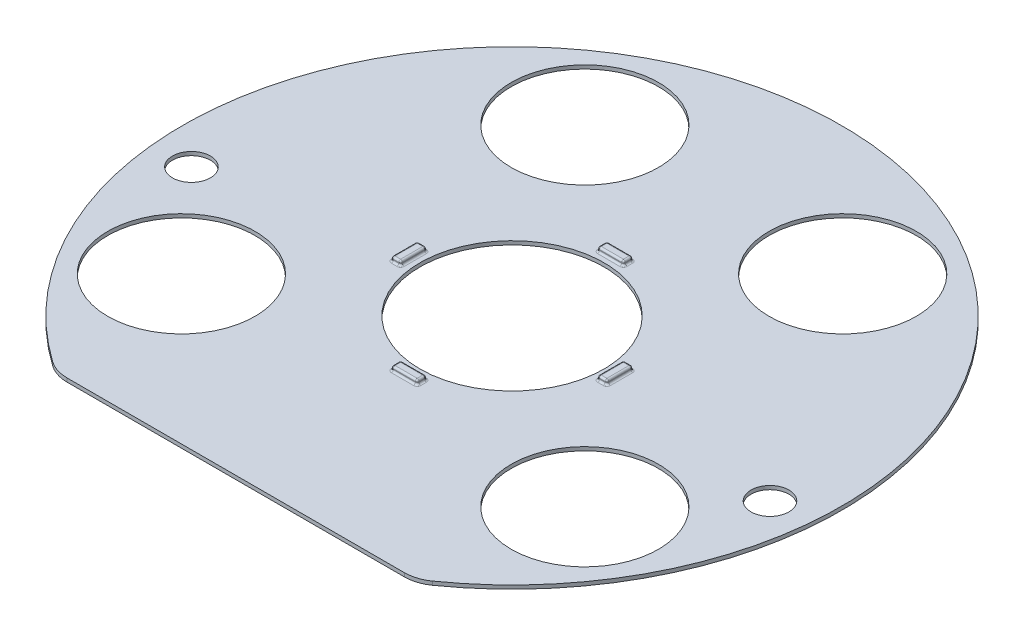
SolidWorks part; units mm, degrees
material "6063-T6"
ref_plane "Front Plane" through (0, 0, 0) normal (0, 0, 1) x (1, 0, 0)
ref_plane "Top Plane" through (0, 0, 0) normal (0, 1, 0) x (1, 0, 0)
ref_plane "Right Plane" through (0, 0, 0) normal (1, 0, 0) x (0, 0, -1)
sketch "Sketch1" plane through (0, 0, 0) normal (0, 1, 0) x (1, 0, 0)
  line L0 (0, 89.5) -> (0, -75) construction
  line L2 (-89.5, 0) -> (89.5, 0) construction
  line L3 (-48.839, -75) -> (48.839, -75)
  arc A0 (48.839, -75) -> (-48.839, -75) centre (0, 0) ccw
  dimension "D1" = 179
  dimension "D2" = 75
extrude "Boss-Extrude1" add sketch "Sketch1" against normal blind 1
sketch "Sketch9" plane through (0, 0, 0) normal (0, 1, 0) x (1, 0, 0)
  line L0 (0, 89.5) -> (0, -75) construction
  line L1 (48.839, -75) -> (-48.839, -75) construction
  line L2 (78.5412, -8.5017) -> (-78.5412, -8.5017) construction
  arc A12 (48.839, -75) -> (-48.839, -75) centre (0, 0) ccw construction
  circle A13 centre (78.5412, -8.5017) radius 5.15
  circle A15 centre (-78.5412, -8.5017) radius 5.15
  point P8 (0, -8.5017)
  dimension "D3" = 10.3
  dimension "D4" = 10.3
  dimension "D2" = 66.4983
  dimension "D1" = 157.0824
extrude "Cut-Extrude3" cut sketch "Sketch9" against normal through all
sketch "Vision Pattern" plane through (0, 0, 0) normal (0, 1, 0) x (1, 0, 0)
  line L0 (64.8074, -55) -> (-64.8074, -55) construction
  line L1 (0, 0) -> (0, -55) construction
  circle A0 centre (0, 0) radius 85 construction
  circle A1 centre (0, 0) radius 25
  circle A2 centre (54.7723, -35) radius 20
  circle A3 centre (-54.7723, -35) radius 20
  circle A4 centre (35, 54.7723) radius 20
  circle A5 centre (-35, 54.7723) radius 20
  circle A6 centre (0, 0) radius 65 construction
  dimension "D1" = 170
  dimension "D3" = 50
  dimension "D4" = 40
  dimension "D2" = 55
  dimension "D5" = 35
  dimension "D8" = 65
  dimension "D6" = 35
  dimension "D7" = 35
extrude "Cut-Extrude4" cut sketch "Vision Pattern" against normal through all
sketch "Sketch10" plane through (0, 0, 0) normal (0, 1, 0) x (1, 0, 0)
  line L0 (0, 28) -> (0, -28) construction
  line L1 (-28, 0) -> (28, 0) construction
  line L2 (3.5, 26.75) -> (-3.5, 26.75)
  line L3 (-26.75, 3.5) -> (-29.25, 3.5)
  line L4 (-26.75, 3.5) -> (-26.75, -3.5)
  line L5 (-26.75, -3.5) -> (-29.25, -3.5)
  line L6 (-29.25, 3.5) -> (-29.25, -3.5)
  line L7 (-26.75, 3.5) -> (-29.25, -3.5) construction
  line L8 (-26.75, -3.5) -> (-29.25, 3.5) construction
  line L9 (3.5, 26.75) -> (3.5, 29.25)
  line L10 (3.5, 29.25) -> (-3.5, 29.25)
  line L11 (-3.5, 26.75) -> (-3.5, 29.25)
  line L12 (26.75, -3.5) -> (26.75, 3.5)
  line L13 (26.75, -3.5) -> (29.25, -3.5)
  line L14 (29.25, -3.5) -> (29.25, 3.5)
  line L15 (26.75, 3.5) -> (29.25, 3.5)
  line L16 (-3.5, -26.75) -> (3.5, -26.75)
  line L17 (-3.5, -26.75) -> (-3.5, -29.25)
  line L18 (-3.5, -29.25) -> (3.5, -29.25)
  line L19 (3.5, -26.75) -> (3.5, -29.25)
  line L20 (-3.5, 29.25) -> (3.5, 26.75) construction
  line L21 (3.5, 29.25) -> (-3.5, 26.75) construction
  point P4 (0, 0)
  point P8 (0, 0)
  point P27 (0, 0)
  dimension "D1" = 56
  dimension "D2" = 7
  dimension "D3" = 2.5
fillet "Fillet1" radius 10 2 edges at (-48.839, -0.5, 75) (48.839, -0.5, 75)
extrude "Boss-Extrude2" add sketch "Sketch10" along normal blind 1.2
fillet "Fillet2" radius 0.5 48 edges at (-3.5, 0.6, 26.75) (3.5, 0.6, 29.25) (3.5, 0.6, 26.75) (26.75, 0.6, 3.5) (29.25, 0.6, 3.5) (29.25, 0.6, -3.5) (26.75, 0.6, -3.5) (3.5, 0.6, -26.75) (3.5, 0.6, -29.25) (-3.5, 0.6, -29.25) (-3.5, 0.6, -26.75) (-26.75, 0.6, 3.5) (-26.75, 0.6, -3.5) (-29.25, 0.6, -3.5) (-29.25, 0.6, 3.5) (-3.5, 0.6, 29.25) (0, 0, -29.25) (29.25, 0, 0) (0, 0, 26.75) (-26.75, 0, 0) (-3.5, 0, -28) (3.5, 0, -28) (28, 0, -3.5) (28, 0, 3.5) (-3.5, 0, 28) (3.5, 0, 28) (-28, 0, -3.5) (-28, 0, 3.5) (0, 1.2, -29.25) (3.5, 1.2, -28) (0, 1.2, -26.75) (-3.5, 1.2, -28) (29.25, 1.2, 0) (28, 1.2, 3.5) (26.75, 1.2, 0) (28, 1.2, -3.5) (0, 1.2, 29.25) (-3.5, 1.2, 28) (0, 1.2, 26.75) (3.5, 1.2, 28) (-28, 1.2, -3.5) (-26.75, 1.2, 0) (-28, 1.2, 3.5) (-29.25, 1.2, 0) (0, 0, -26.75) (26.75, 0, 0) (0, 0, 29.25) (-29.25, 0, 0)
equation "\"D4@Sketch9\"=\"D3@Sketch9\""
equation "\"D1@Vision Pattern\" = 85 * 2"
equation "\"D7@Vision Pattern\"=\"D6@Vision Pattern\""
equation "\"20Gauge\"= .911"
equation "\"Tab-Distance\"=56"
equation "\"D1@Sketch10\"=\"Tab-Distance\""
